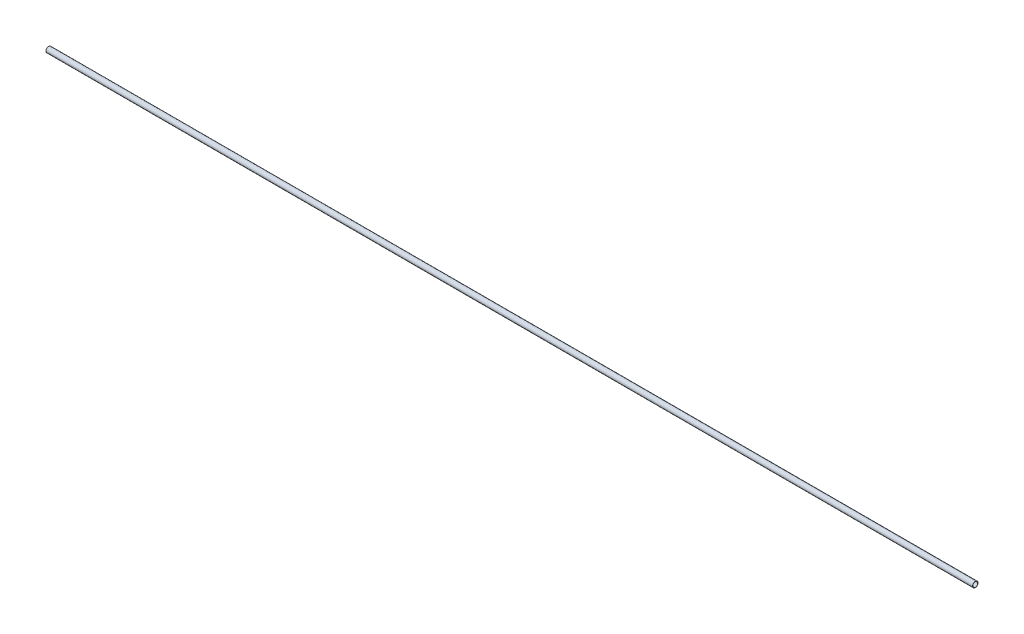
SolidWorks part; units mm, degrees
material "Galvanized Steel"
ref_plane "Front Plane" through (0, 0, 0) normal (0, 0, 1) x (1, 0, 0)
ref_plane "Top Plane" through (0, 0, 0) normal (0, 1, 0) x (1, 0, 0)
ref_plane "Right Plane" through (0, 0, 0) normal (1, 0, 0) x (0, 0, -1)
sketch "Sketch1" plane through (0, 0, 0) normal (1, 0, 0) x (0, 0, -1)
  circle A0 centre (0, 0) radius 7.8994
  circle A1 centre (0, 0) radius 8.9662
  dimension "D1" = 15.7988
  dimension "D2" = 17.9324
extrude "Boss-Extrude1" add sketch "Sketch1" along normal blind 3048
